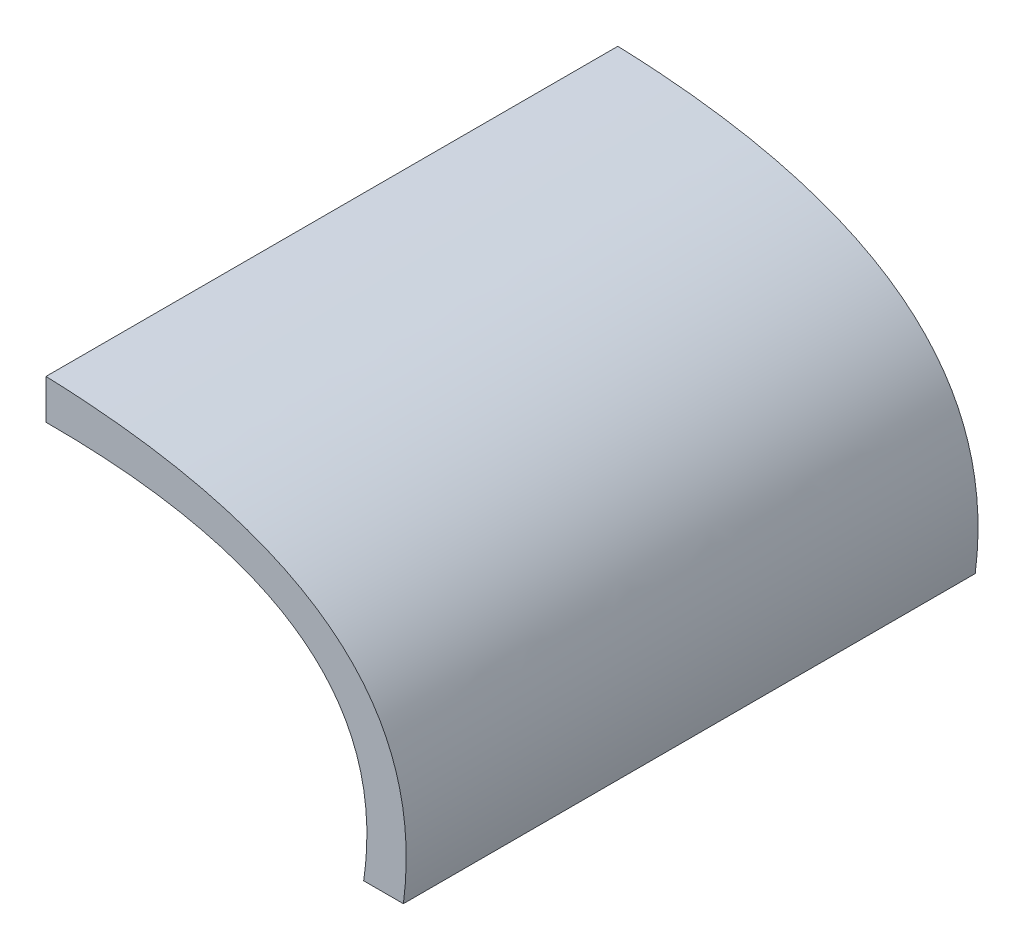
SolidWorks part; units mm, degrees
ref_plane "Front Plane" through (0, 0, 0) normal (0, 0, 1) x (1, 0, 0)
ref_plane "Top Plane" through (0, 0, 0) normal (0, 1, 0) x (1, 0, 0)
ref_plane "Right Plane" through (0, 0, 0) normal (1, 0, 0) x (0, 0, -1)
sketch "Sketch1" plane through (0, 0, 0) normal (0, 0, 1) x (1, 0, 0)
  line L0 (0, 0) -> (0, 35) construction
  line L1 (0, 0) -> (45, 0) construction
  line L2 (45, 0) -> (45, 10) construction
  line L3 (45, 10) -> (0, 10) construction
  line L4 (0, 35) -> (0, 30) construction
  line L5 (45, 10) -> (40, 10) construction
  line L6 (40, 10) -> (40, 0) construction
  line L7 (0, 35) -> (0, 30)
  line L8 (40, 0) -> (45, 0)
  spline S0 degree 2 poles (0, 35) (49.3708, 33.3109) (45, 0) knots 0 0 0 1 1 1
  spline S1 degree 2 poles (0, 30) (44.4721, 30.1246) (40, 0) knots 0 0 0 1 1 1
extrude "Boss-Extrude1" add sketch "Sketch1" along normal blind 72
